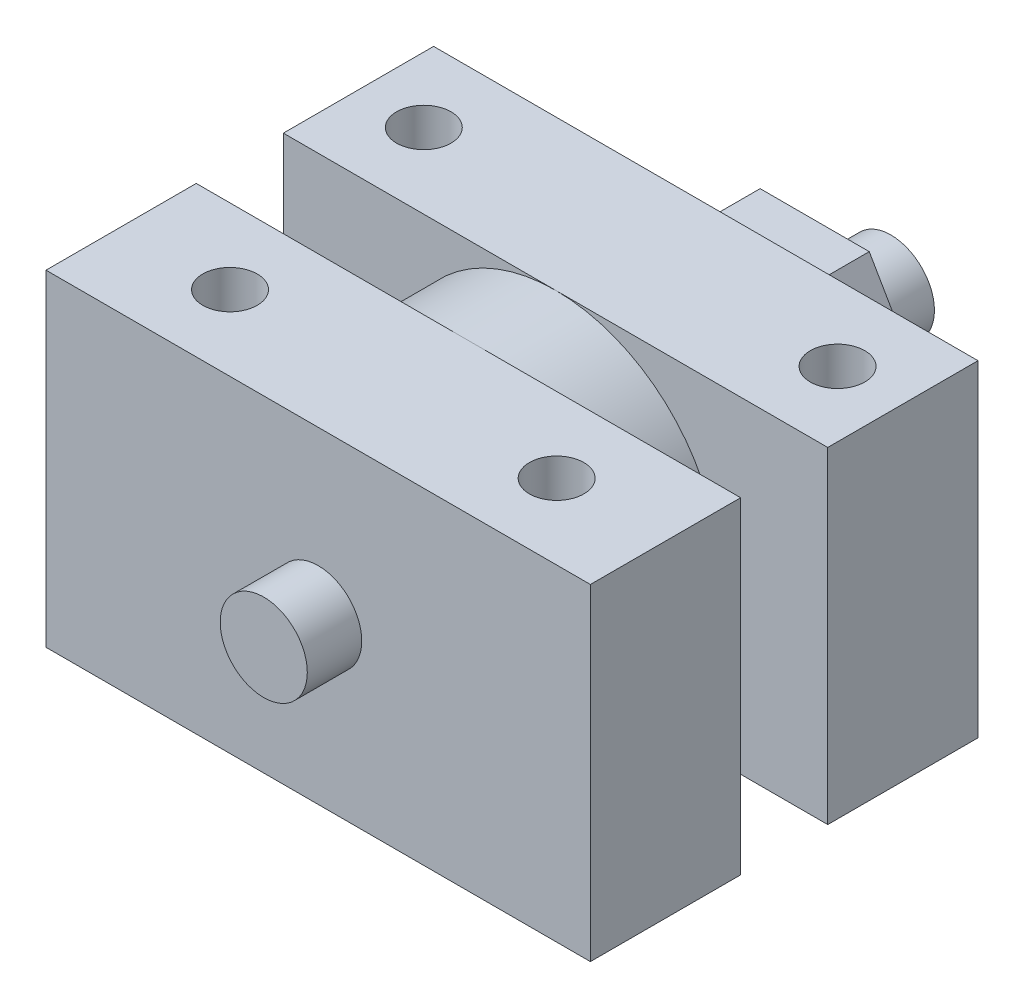
SolidWorks part; units mm, degrees
material "AISI 304"
ref_plane "前视基准面" through (0, 0, 0) normal (0, 0, 1) x (1, 0, 0)
ref_plane "上视基准面" through (0, 0, 0) normal (0, 1, 0) x (1, 0, 0)
ref_plane "右视基准面" through (0, 0, 0) normal (1, 0, 0) x (0, 0, -1)
sketch "草图1" plane through (0, 0, 0) normal (0, 1, 0) x (1, 0, 0)
  line L0 (0, 10.9) -> (0, -10.9) construction
  line L5 (-19, 10.9) -> (19, 10.9) construction
  line L6 (-25, 17.8) -> (25, 17.8)
  line L7 (-25, 17.8) -> (-25, 4)
  line L8 (-25, 4) -> (25, 4)
  line L9 (25, 17.8) -> (25, 4)
  line L10 (-25, 17.8) -> (25, 4) construction
  line L11 (-25, 4) -> (25, 17.8) construction
  line L12 (-25, -4) -> (25, -4)
  line L13 (-25, -4) -> (-25, -17.8)
  line L14 (-25, -17.8) -> (25, -17.8)
  line L15 (25, -4) -> (25, -17.8)
  line L16 (-25, -4) -> (25, -17.8) construction
  line L17 (-25, -17.8) -> (25, -4) construction
  line L18 (-15, -10.9) -> (15, -10.9) construction
  circle A0 centre (-19, 10.9) radius 2.5
  circle A1 centre (19, 10.9) radius 2.5
  circle A2 centre (15, -10.9) radius 2.5
  circle A3 centre (-15, -10.9) radius 2.5
  point P3 (0, 0)
  point P16 (0, 10.9)
  point P20 (0, -10.9)
  dimension "D6" = 5
  dimension "D1" = 21.8
  dimension "D2" = 35.6
  dimension "D3" = 50
  dimension "D4" = 38
  dimension "D5" = 30
extrude "凸台-拉伸1" add sketch "草图1" along normal mid plane 30
sketch "草图2" plane through (0, 0, 0) normal (0, 0, 1) x (1, 0, 0)
  line L0 (-25, 15) -> (25, 15) construction
  circle A0 centre (0, 0) radius 15
extrude "凸台-拉伸2" add sketch "草图2" along normal up to next and the other way up to next
ref_plane "基准面1" through (0, 0, 22.8) normal (0, 0, 1) x (1, 0, 0)
sketch "草图3" plane through (0, 0, 22.8) normal (0, 0, 1) x (1, 0, 0)
  circle A0 centre (0, 0) radius 4
  dimension "D1" = 8
extrude "凸台-拉伸3" add sketch "草图3" against normal blind 57.6
sketch "草图4" plane through (0, 0, -17.8) normal (0, 0, -1) x (-1, 0, 0)
  line L1 (-10.0219, 0) -> (-5.011, -8.6793)
  line L2 (-5.011, -8.6793) -> (5.011, -8.6793)
  line L3 (5.011, -8.6793) -> (10.0219, 0)
  line L4 (10.0219, 0) -> (5.011, 8.6793)
  line L5 (5.011, 8.6793) -> (-5.011, 8.6793)
  line L6 (-5.011, 8.6793) -> (-10.0219, 0)
  circle A0 centre (0, 0) radius 8.6793 construction
extrude "凸台-拉伸4" add sketch "草图4" along normal blind 10
